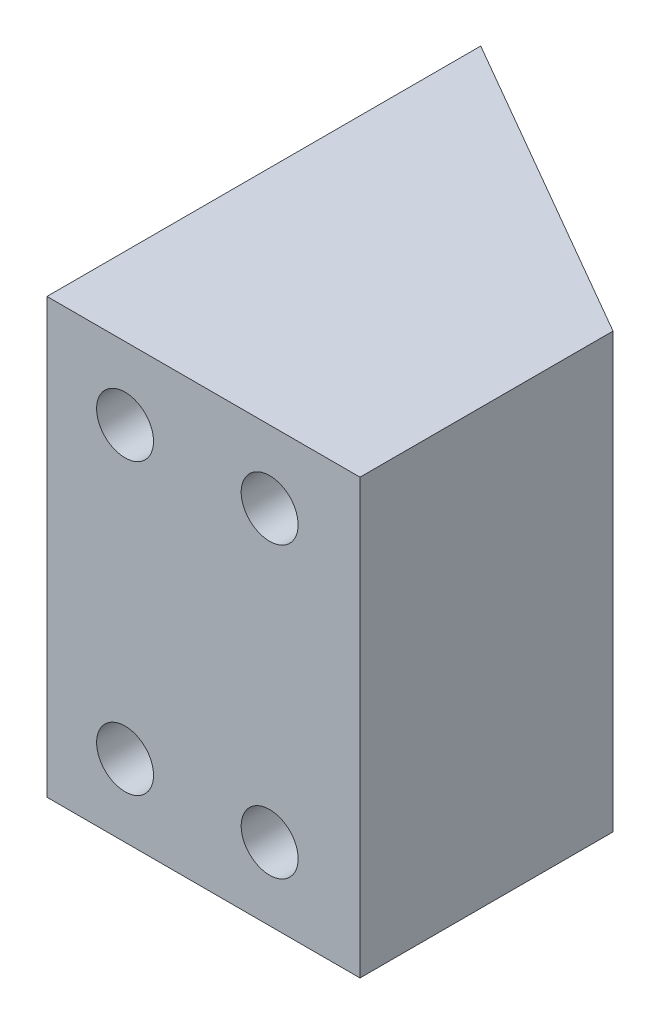
SolidWorks part; units mm, degrees
ref_plane "Front Plane" through (0, 0, 0) normal (0, 0, 1) x (1, 0, 0)
ref_plane "Top Plane" through (0, 0, 0) normal (0, 1, 0) x (1, 0, 0)
ref_plane "Right Plane" through (0, 0, 0) normal (1, 0, 0) x (0, 0, -1)
sketch "Sketch2" plane through (0, 0, 0) normal (0, 1, 0) x (1, 0, 0)
  line L0 (0, 0) -> (0, -20)
  line L1 (0, -20) -> (34.641, -20) construction
  line L2 (34.641, -20) -> (0, 0)
  line L5 (0, -20) -> (0, -48)
  line L6 (0, -48) -> (34.641, -48)
  line L7 (34.641, -20) -> (34.641, -48)
  line L8 (17.3205, -48) -> (17.3205, -20) construction
  line L9 (0, -34) -> (34.641, -34) construction
  point P282 (17.3205, -34)
  dimension "D1" = 40
  dimension "D2" = 30
  dimension "D3" = 28
extrude "Boss-Extrude1" add sketch "Sketch2" along normal blind 48
sketch "Sketch3" plane through (0, 0, 0) normal (0.5, 0, -0.866) x (-0.866, 0, -0.5)
  line L0 (-7, 40) -> (-7, 8) construction
  line L1 (-54, 24) -> (0, 24) construction
  line L3 (0, 48) -> (0, 0) construction
  line L4 (-54, 48) -> (-54, 0) construction
  circle A0 centre (-7, 40) radius 4.1
  circle A1 centre (-7, 8) radius 4.1
  point P4 (-7, 24)
  dimension "D2" = 8.2
  dimension "D1" = 32
  dimension "D4" = 7
extrude "Cut-Extrude1" cut sketch "Sketch3" against normal blind 41.7
sketch "Sketch4" plane through (0, 0, 48) normal (0, 0, 1) x (1, 0, 0)
  line L0 (0, 48) -> (34.641, 48) construction
  line L1 (8.641, 40) -> (24.641, 40) construction
  line L2 (8.641, 40) -> (8.641, 8) construction
  line L3 (8.641, 8) -> (24.641, 8) construction
  line L4 (24.641, 40) -> (24.641, 8) construction
  line L5 (16.641, 8) -> (16.641, 40) construction
  line L6 (8.641, 24) -> (24.641, 24) construction
  line L7 (34.641, 48) -> (34.641, 0) construction
  circle A0 centre (8.641, 40) radius 3.15
  circle A1 centre (24.641, 40) radius 3.15
  circle A2 centre (8.641, 8) radius 3.15
  circle A3 centre (24.641, 8) radius 3.15
  point P197 (16.641, 24)
  dimension "D1" = 6.3
  dimension "D2" = 6.3
  dimension "D3" = 6.3
  dimension "D4" = 6.3
  dimension "D5" = 16
  dimension "D6" = 32
  dimension "D7" = 8
  dimension "D8" = 10
extrude "Cut-Extrude2" cut sketch "Sketch4" against normal blind 4.7
sketch "Sketch5" plane through (0, 0, 0) normal (0.5, 0, -0.866) x (-0.866, 0, -0.5)
  circle A0 centre (-7, 40) radius 4.1
  circle A1 centre (-7, 40) radius 2.1
  circle A2 centre (-7, 8) radius 4.1
  circle A3 centre (-7, 8) radius 2.1
  circle A4 centre (-7, 8) radius 4.1 construction
  circle A5 centre (-7, 40) radius 4.1 construction
  dimension "D1" = 4.2
  dimension "D2" = 4.2
extrude "Boss-Extrude2" add sketch "Sketch5" against normal blind 3
